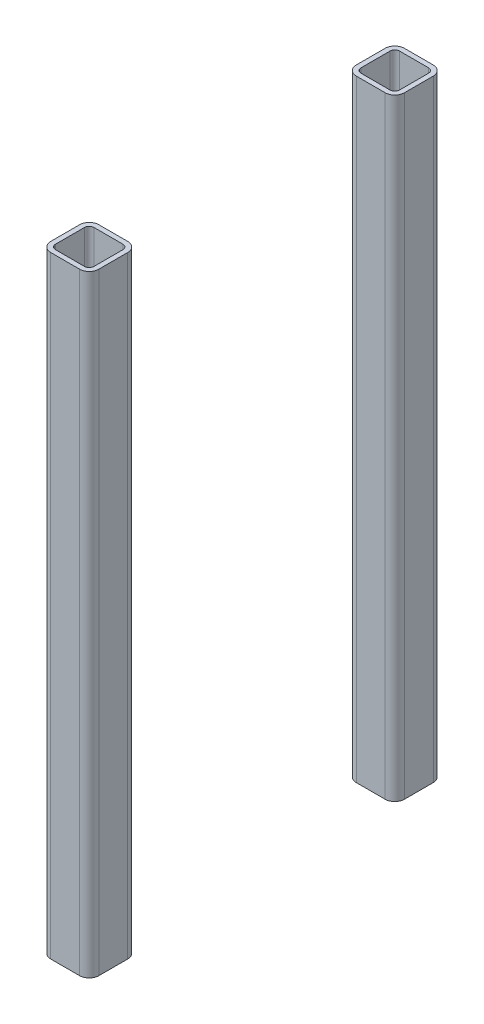
SolidWorks part; units mm, degrees
ref_plane "Front Plane" through (0, 0, 0) normal (0, 0, 1) x (1, 0, 0)
ref_plane "Top Plane" through (0, 0, 0) normal (0, 1, 0) x (1, 0, 0)
ref_plane "Right Plane" through (0, 0, 0) normal (1, 0, 0) x (0, 0, -1)
sketch "Sketch1" plane through (0, 0, 0) normal (0, 1, 0) x (1, 0, 0)
  line L1 (854.075, -850.011) -> (-854.075, -850.011)
  line L2 (854.075, -850.011) -> (854.075, 850.011)
  line L3 (854.075, 850.011) -> (-854.075, 850.011)
  line L4 (-854.075, -850.011) -> (-854.075, 850.011)
  line L5 (854.075, -850.011) -> (-854.075, 850.011) construction
  line L6 (854.075, 850.011) -> (-854.075, -850.011) construction
  point P0 (0, 0)
  dimension "D1" = 1708.15
  dimension "D2" = 1700.022
sketch3d "3DSketch1"
  line L0 (-854.075, 0, -850.011) -> (854.075, 0, -850.011)
  line L1 (854.075, 0, -850.011) -> (854.075, 0, 850.011)
  line L2 (854.075, 0, 850.011) -> (-854.075, 0, 850.011)
  line L3 (-854.075, 0, 850.011) -> (-854.075, 0, -850.011)
  line L4 (0, 0, -850.011) -> (0, 0, 850.011)
  line L5 (0, 0, 0) -> (0, -508.6162, 0)
  line L6 (0, 0, -254) -> (0, -508.6162, -254)
other "Square tube 40 X 40 X 4(2)"
ref_plane "Plane5" through (0, 0, -254) normal (0, -1, 0) x (1, 0, 0)
sketch "Sketch13" plane through (0, 0, -254) normal (0, -1, 0) x (1, 0, 0)
  line L0 (-12, -16) -> (12, -16)
  line L1 (-16, -12) -> (-16, 12)
  line L2 (12, 16) -> (-12, 16)
  line L3 (16, 12) -> (16, -12)
  line L4 (-12, -20) -> (12, -20)
  line L5 (-20, -12) -> (-20, 12)
  line L6 (12, 20) -> (-12, 20)
  line L7 (20, 12) -> (20, -12)
  arc A0 (20, 12) -> (12, 20) centre (12, 12) ccw
  arc A1 (12, -20) -> (20, -12) centre (12, -12) ccw
  arc A2 (-20, -12) -> (-12, -20) centre (-12, -12) ccw
  arc A3 (-12, 20) -> (-20, 12) centre (-12, 12) ccw
  arc A4 (-12, 16) -> (-16, 12) centre (-12, 12) ccw
  arc A5 (16, 12) -> (12, 16) centre (12, 12) ccw
  arc A6 (12, -16) -> (16, -12) centre (12, -12) ccw
  arc A7 (-16, -12) -> (-12, -16) centre (-12, -12) ccw
  point P0 (-20, 0)
  point P1 (20, 0)
  point P2 (0, 20)
  point P3 (0, -20)
  point P4 (0, 0)
  point P5 (-20, -20)
  point P6 (20, -20)
  point P7 (20, 20)
  point P8 (-20, 20)
  point P33 (0, 0)
  dimension "D1" = 8
  dimension "Thickness" = 4
  dimension "V_leg" = 40
